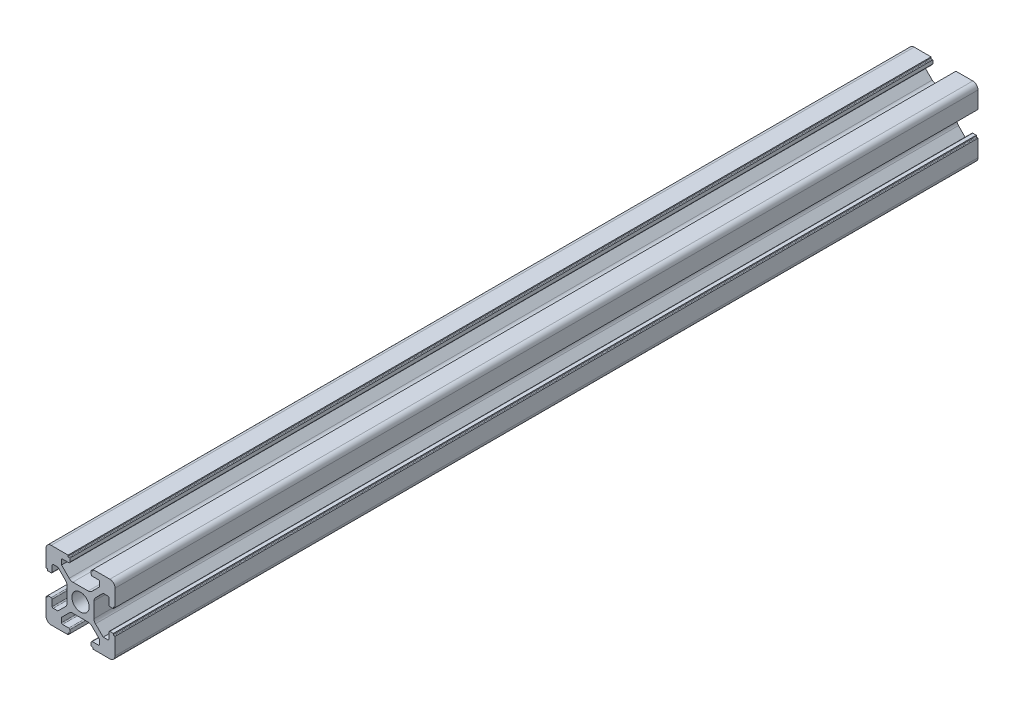
SolidWorks part; units mm, degrees
ref_plane "前视基准面" through (0, 0, 0) normal (0, 0, 1) x (1, 0, 0)
ref_plane "上视基准面" through (0, 0, 0) normal (0, 1, 0) x (1, 0, 0)
ref_plane "右视基准面" through (0, 0, 0) normal (1, 0, 0) x (0, 0, -1)
sketch "草图1" plane through (0, 0, 0) normal (0, 0, 1) x (1, 0, 0)
  line L0 (4.216, 3.2442) -> (6.4367, 5.4649)
  line L1 (6.4367, 5.4649) -> (7.7767, 5.4649)
  line L2 (8.0767, 5.1649) -> (8.0767, 3.3649)
  line L3 (8.3767, 3.0649) -> (9.3767, 3.0649)
  line L4 (9.3767, 3.0649) -> (9.3767, 3.3649)
  line L5 (9.5767, 3.5649) -> (9.8767, 3.5649)
  line L6 (9.8767, 3.5649) -> (9.8767, 8.4649)
  line L7 (8.3767, 9.9649) -> (3.4767, 9.9649)
  line L8 (3.4767, 9.9649) -> (3.4767, 9.6649)
  line L9 (3.2767, 9.4649) -> (2.9767, 9.4649)
  line L10 (2.9767, 9.4649) -> (2.9767, 8.4649)
  line L11 (3.2767, 8.1649) -> (5.0767, 8.1649)
  line L12 (5.3767, 7.8649) -> (5.3767, 6.5249)
  line L13 (5.3767, 6.5249) -> (3.156, 4.3042)
  line L14 (2.0953, 3.8649) -> (-2.342, 3.8649)
  line L15 (-3.4027, 4.3042) -> (-5.6233, 6.5249)
  line L16 (-5.6233, 6.5249) -> (-5.6233, 7.8649)
  line L17 (-5.3233, 8.1649) -> (-3.5233, 8.1649)
  line L18 (-3.2233, 8.4649) -> (-3.2233, 9.4649)
  line L19 (-3.2233, 9.4649) -> (-3.5233, 9.4649)
  line L20 (-3.7233, 9.6649) -> (-3.7233, 9.9649)
  line L21 (-3.7233, 9.9649) -> (-8.6233, 9.9649)
  line L22 (-10.1233, 8.4649) -> (-10.1233, 3.5649)
  line L23 (-10.1233, 3.5649) -> (-9.8233, 3.5649)
  line L24 (-9.6233, 3.3649) -> (-9.6233, 3.0649)
  line L25 (-9.6233, 3.0649) -> (-8.6233, 3.0649)
  line L26 (-8.3233, 3.3649) -> (-8.3233, 5.1649)
  line L27 (-8.0233, 5.4649) -> (-6.6833, 5.4649)
  line L28 (-6.6833, 5.4649) -> (-4.4627, 3.2442)
  line L29 (-4.0233, 2.1836) -> (-4.0233, -2.2538)
  line L30 (-4.4627, -3.3144) -> (-6.6833, -5.5351)
  line L31 (-6.6833, -5.5351) -> (-8.0233, -5.5351)
  line L32 (-8.3233, -5.2351) -> (-8.3233, -3.4351)
  line L33 (-8.6233, -3.1351) -> (-9.6233, -3.1351)
  line L34 (-9.6233, -3.1351) -> (-9.6233, -3.4351)
  line L35 (-9.8233, -3.6351) -> (-10.1233, -3.6351)
  line L36 (-10.1233, -3.6351) -> (-10.1233, -8.5351)
  line L37 (-8.6233, -10.0351) -> (-3.7233, -10.0351)
  line L38 (-3.7233, -10.0351) -> (-3.7233, -9.7351)
  line L39 (-3.5233, -9.5351) -> (-3.2233, -9.5351)
  line L40 (-3.2233, -9.5351) -> (-3.2233, -8.5351)
  line L41 (-3.5233, -8.2351) -> (-5.3233, -8.2351)
  line L42 (-5.6233, -7.9351) -> (-5.6233, -6.5951)
  line L43 (-5.6233, -6.5951) -> (-3.4027, -4.3744)
  line L44 (-2.342, -3.9351) -> (2.0953, -3.9351)
  line L45 (3.156, -4.3744) -> (5.3767, -6.5951)
  line L46 (5.3767, -6.5951) -> (5.3767, -7.9351)
  line L47 (5.0767, -8.2351) -> (3.2767, -8.2351)
  line L48 (2.9767, -8.5351) -> (2.9767, -9.5351)
  line L49 (2.9767, -9.5351) -> (3.2767, -9.5351)
  line L50 (3.4767, -9.7351) -> (3.4767, -10.0351)
  line L51 (3.4767, -10.0351) -> (8.3767, -10.0351)
  line L52 (9.8767, -8.5351) -> (9.8767, -3.6351)
  line L53 (9.8767, -3.6351) -> (9.5767, -3.6351)
  line L54 (9.3767, -3.4351) -> (9.3767, -3.1351)
  line L55 (9.3767, -3.1351) -> (8.3767, -3.1351)
  line L56 (8.0767, -3.4351) -> (8.0767, -5.2351)
  line L57 (7.7767, -5.5351) -> (6.4367, -5.5351)
  line L58 (6.4367, -5.5351) -> (4.216, -3.3144)
  line L59 (3.7767, -2.2538) -> (3.7767, 2.1836)
  circle A0 centre (-0.1233, -0.0351) radius 2.5
  arc A1 (8.0767, 5.1649) -> (7.7767, 5.4649) centre (7.7767, 5.1649) ccw
  arc A2 (8.0767, 3.3649) -> (8.3767, 3.0649) centre (8.3767, 3.3649) ccw
  arc A3 (9.5767, 3.5649) -> (9.3767, 3.3649) centre (9.5767, 3.3649) ccw
  arc A4 (9.8767, 8.4649) -> (8.3767, 9.9649) centre (8.3767, 8.4649) ccw
  arc A5 (3.2767, 9.4649) -> (3.4767, 9.6649) centre (3.2767, 9.6649) ccw
  arc A6 (2.9767, 8.4649) -> (3.2767, 8.1649) centre (3.2767, 8.4649) ccw
  arc A7 (5.3767, 7.8649) -> (5.0767, 8.1649) centre (5.0767, 7.8649) ccw
  arc A8 (2.0953, 3.8649) -> (3.156, 4.3042) centre (2.0953, 5.3649) ccw
  arc A9 (-3.4027, 4.3042) -> (-2.342, 3.8649) centre (-2.342, 5.3649) ccw
  arc A10 (-5.3233, 8.1649) -> (-5.6233, 7.8649) centre (-5.3233, 7.8649) ccw
  arc A11 (-3.5233, 8.1649) -> (-3.2233, 8.4649) centre (-3.5233, 8.4649) ccw
  arc A12 (-3.7233, 9.6649) -> (-3.5233, 9.4649) centre (-3.5233, 9.6649) ccw
  arc A13 (-8.6233, 9.9649) -> (-10.1233, 8.4649) centre (-8.6233, 8.4649) ccw
  arc A14 (-9.6233, 3.3649) -> (-9.8233, 3.5649) centre (-9.8233, 3.3649) ccw
  arc A15 (-8.6233, 3.0649) -> (-8.3233, 3.3649) centre (-8.6233, 3.3649) ccw
  arc A16 (-8.0233, 5.4649) -> (-8.3233, 5.1649) centre (-8.0233, 5.1649) ccw
  arc A17 (-4.0233, 2.1836) -> (-4.4627, 3.2442) centre (-5.5233, 2.1836) ccw
  arc A18 (-4.4627, -3.3144) -> (-4.0233, -2.2538) centre (-5.5233, -2.2538) ccw
  arc A19 (-8.3233, -5.2351) -> (-8.0233, -5.5351) centre (-8.0233, -5.2351) ccw
  arc A20 (-8.3233, -3.4351) -> (-8.6233, -3.1351) centre (-8.6233, -3.4351) ccw
  arc A21 (-9.8233, -3.6351) -> (-9.6233, -3.4351) centre (-9.8233, -3.4351) ccw
  arc A22 (-10.1233, -8.5351) -> (-8.6233, -10.0351) centre (-8.6233, -8.5351) ccw
  arc A23 (-3.5233, -9.5351) -> (-3.7233, -9.7351) centre (-3.5233, -9.7351) ccw
  arc A24 (-3.2233, -8.5351) -> (-3.5233, -8.2351) centre (-3.5233, -8.5351) ccw
  arc A25 (-5.6233, -7.9351) -> (-5.3233, -8.2351) centre (-5.3233, -7.9351) ccw
  arc A26 (-2.342, -3.9351) -> (-3.4027, -4.3744) centre (-2.342, -5.4351) ccw
  arc A27 (3.156, -4.3744) -> (2.0953, -3.9351) centre (2.0953, -5.4351) ccw
  arc A28 (5.0767, -8.2351) -> (5.3767, -7.9351) centre (5.0767, -7.9351) ccw
  arc A29 (3.2767, -8.2351) -> (2.9767, -8.5351) centre (3.2767, -8.5351) ccw
  arc A30 (3.4767, -9.7351) -> (3.2767, -9.5351) centre (3.2767, -9.7351) ccw
  arc A31 (8.3767, -10.0351) -> (9.8767, -8.5351) centre (8.3767, -8.5351) ccw
  arc A32 (9.3767, -3.4351) -> (9.5767, -3.6351) centre (9.5767, -3.4351) ccw
  arc A33 (8.3767, -3.1351) -> (8.0767, -3.4351) centre (8.3767, -3.4351) ccw
  arc A34 (7.7767, -5.5351) -> (8.0767, -5.2351) centre (7.7767, -5.2351) ccw
  arc A35 (3.7767, -2.2538) -> (4.216, -3.3144) centre (5.2767, -2.2538) ccw
  arc A36 (4.216, 3.2442) -> (3.7767, 2.1836) centre (5.2767, 2.1836) ccw
extrude "凸台-拉伸1" add sketch "草图1" along normal blind 250
